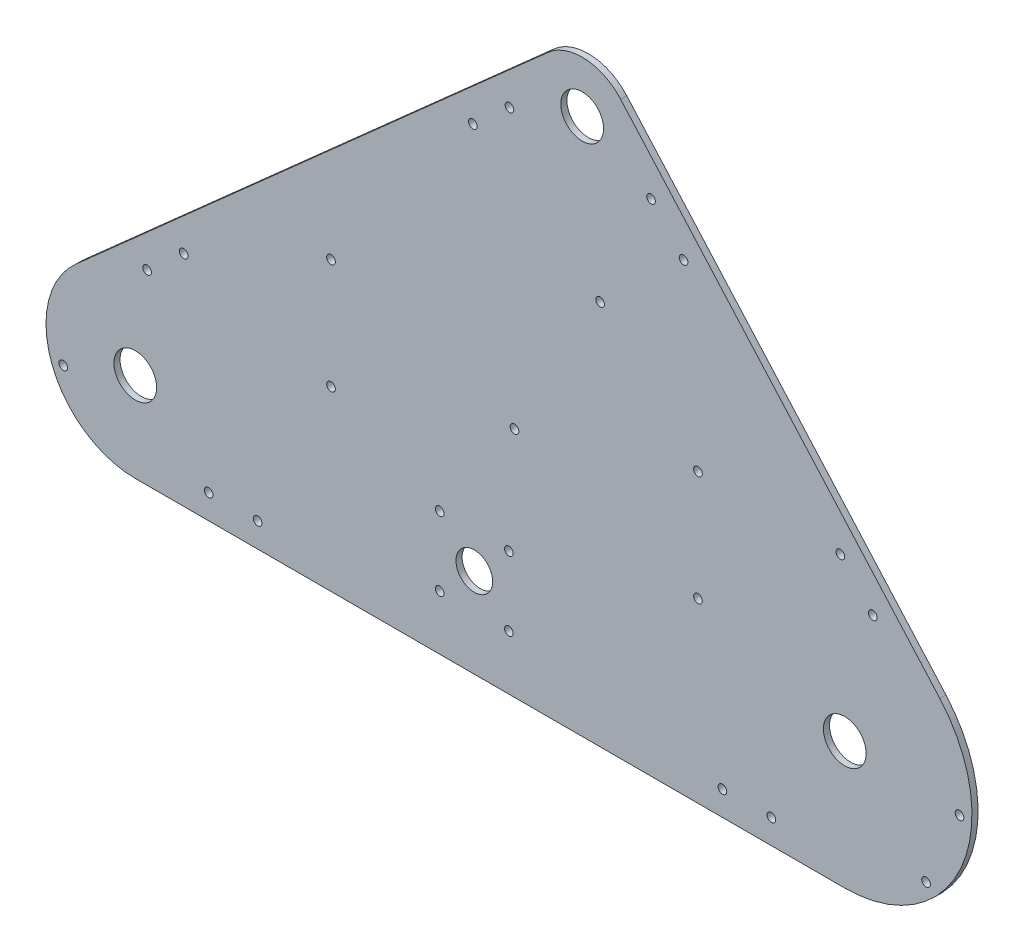
SolidWorks part; units mm, degrees
ref_plane "Front Plane" through (0, 0, 0) normal (0, 0, 1) x (1, 0, 0)
ref_plane "Top Plane" through (0, 0, 0) normal (0, 1, 0) x (1, 0, 0)
ref_plane "Right Plane" through (0, 0, 0) normal (1, 0, 0) x (0, 0, -1)
sketch "Sketch1" plane through (0, 0, 0) normal (0, 0, 1) x (1, 0, 0)
  line L4 (-188.2646, 81.0118) -> (56.8098, 298.7045)
  line L5 (-157.48, 0) -> (210.82, 0)
  line L9 (94.461, 296.4767) -> (260.194, 109.8976)
  line L10 (-157.48, 46.355) -> (18.5166, 46.355) construction
  line L11 (15.767, 41.5925) -> (21.2662, 41.5925) construction
  line L12 (21.2662, 41.5925) -> (24.0159, 46.355) construction
  line L13 (24.0159, 46.355) -> (21.2662, 51.1175) construction
  line L14 (21.2662, 51.1175) -> (15.767, 51.1175) construction
  line L15 (15.767, 51.1175) -> (13.0173, 46.355) construction
  line L16 (13.0173, 46.355) -> (15.767, 41.5925) construction
  line L19 (0.5561, 64.3155) -> (36.4771, 64.3155) construction
  line L20 (0.5561, 64.3155) -> (0.5561, 28.3945) construction
  line L21 (0.5561, 28.3945) -> (36.4771, 28.3945) construction
  line L22 (36.4771, 64.3155) -> (36.4771, 28.3945) construction
  line L23 (0.5561, 64.3155) -> (36.4771, 28.3945) construction
  line L24 (0.5561, 28.3945) -> (36.4771, 64.3155) construction
  arc A3 (-188.2646, 81.0118) -> (-157.48, 0) centre (-157.48, 46.355) ccw
  arc A4 (210.82, 0) -> (260.194, 109.8976) centre (210.82, 66.04) ccw
  arc A5 (94.461, 296.4767) -> (56.8098, 298.7045) centre (74.5215, 278.765) ccw
  circle A7 centre (-157.48, 46.355) radius 11.0998
  circle A8 centre (74.5215, 278.765) radius 11.0998
  circle A9 centre (210.82, 66.04) radius 11.0998
  circle A10 centre (18.5166, 46.355) radius 4.7625 construction
  circle A11 centre (18.5166, 46.355) radius 9.525
  point P0 (32.5752, -12.4288)
  point P2 (0, 0)
  point P29 (103.7153, 222.8013)
  point P51 (0, 0)
  point P53 (69.8235, 270.9052)
  point P54 (0, 0)
  point P55 (0, 0)
  dimension "D3" = 19.685
  dimension "D4" = 90
  dimension "D5" = 232.41
  dimension "D2" = 368.3
  dimension "D6" = 92.71
  dimension "D7" = 53.34
  dimension "D8" = 132.08
  dimension "D10" = 22.1996
  dimension "D11" = 9.525
  dimension "D14" = 50.8
  dimension "D12" = 19.05
  dimension "D13" = 175.9966
extrude "Boss-Extrude1" add sketch "Sketch1" along normal blind 3.175
hole_wizard "#8 Clearance Hole1" positions "Sketch4" profile "Sketch5" hole size "#8" standard "ANSI Inch"
sketch "Sketch4" plane through (0, 0, 3.175) normal (0, 0, 1) x (1, 0, 0)
  point P0 (36.4771, 64.3155)
  point P3 (36.4771, 28.3945)
  point P6 (0.5561, 28.3945)
  point P9 (0.5561, 64.3155)
sketch "Sketch5" plane through (36.4771, 64.3155, 3.175) normal (1, 0, 0) x (0, -1, 0)
  line L0 (0, 0) -> (0, 14.0507)
  line L1 (0, 14.0507) -> (2.2479, 12.7)
  line L2 (2.2479, 12.7) -> (2.2479, 0)
  line L5 (2.2479, 0) -> (0, 0)
  line L10 (0, 14.0507) -> (-2.2479, 12.7) construction
  line L11 (0, -6.35) -> (0, 107.95) construction
  dimension "Hole Dia." = 4.4958
  dimension "Hole Depth" = 12.7
  dimension "Drill Angle" = 118
sketch "Sketch6" plane through (0, 0, 3.175) normal (0, 0, 1) x (1, 0, 0)
  line L0 (56.8098, 298.7045) -> (-188.2646, 81.0118) construction
  line L1 (-157.48, 0) -> (210.82, 0) construction
  line L2 (260.194, 109.8976) -> (94.461, 296.4767) construction
  line L3 (-157.48, 46.355) -> (-188.2646, 81.0118) construction
  line L4 (-157.48, 46.355) -> (-157.48, 0) construction
  line L5 (210.82, 66.04) -> (210.82, 0) construction
  line L6 (210.82, 66.04) -> (260.194, 109.8976) construction
  line L7 (74.5215, 278.765) -> (56.8098, 298.7045) construction
  line L8 (94.461, 296.4767) -> (260.194, 109.8976) construction
  line L10 (74.5215, 278.765) -> (94.461, 296.4767) construction
  line L11 (39.37, 283.2132) -> (39.37, 0) construction
  line L12 (-188.2646, 81.0118) -> (56.8098, 298.7045) construction
  line L13 (-157.48, 0) -> (210.82, 0) construction
  line L14 (210.82, 66.04) -> (276.7447, 62.1393) construction
  line L15 (134.62, 92.075) -> (-55.88, 92.075) construction
  line L16 (134.62, 92.075) -> (134.62, 149.225) construction
  line L17 (134.62, 149.225) -> (-55.88, 149.225) construction
  line L18 (-55.88, 92.075) -> (-55.88, 149.225) construction
  line L19 (134.62, 92.075) -> (-55.88, 149.225) construction
  line L20 (134.62, 149.225) -> (-55.88, 92.075) construction
  line L21 (210.82, 66.04) -> (257.5173, 19.3427) construction
  line L22 (-157.48, 46.355) -> (-200.8119, 29.8888) construction
  arc A0 (210.82, 0) -> (260.194, 109.8976) centre (210.82, 66.04) ccw construction
  arc A1 (-188.2646, 81.0118) -> (-157.48, 0) centre (-157.48, 46.355) ccw construction
  point P0 (-119.38, 12.7)
  point P1 (-93.98, 12.7)
  point P2 (147.32, 12.7)
  point P3 (172.72, 12.7)
  point P4 (-151.3455, 96.8192)
  point P5 (-132.3555, 113.6875)
  point P6 (17.7689, 247.0388)
  point P7 (36.7589, 263.9071)
  point P8 (110.2685, 259.5575)
  point P9 (127.1368, 240.5675)
  point P12 (208.5283, 148.9385)
  point P13 (225.3966, 129.9484)
  point P44 (39.37, 120.65)
  point P50 (83.82, 200.025)
  point P60 (-194.876, 32.1444)
  point P61 (270.3947, 62.515)
  point P62 (253.0272, 23.8328)
  dimension "D28" = 6.35
  dimension "D1" = 12.7
  dimension "D2" = 12.7
  dimension "D3" = 12.7
  dimension "D4" = 12.7
  dimension "D5" = 12.7
  dimension "D6" = 25.4
  dimension "D7" = 38.1
  dimension "D8" = 38.1
  dimension "D9" = 25.4
  dimension "D10" = 25.4
  dimension "D11" = 12.7
  dimension "D12" = 12.7
  dimension "D13" = 25.4
  dimension "D14" = 38.1
  dimension "D15" = 12.7
  dimension "D16" = 12.7
  dimension "D17" = 38.1
  dimension "D18" = 25.4
  dimension "D19" = 25.4
  dimension "D20" = 38.1
  dimension "D21" = 38.1
  dimension "D22" = 196.85
  dimension "D23" = 57.15
  dimension "D24" = 190.5
  dimension "D25" = 120.65
  dimension "D26" = 45
  dimension "D27" = 45
  dimension "D29" = 6.35
  dimension "D30" = 6.35
  dimension "D31" = 50.8
  dimension "D32" = 50.8
hole_wizard "#8 Clearance Hole2" positions "Sketch7" profile "Sketch8" hole size "#8" standard "ANSI Inch" end condition through all
sketch "Sketch7" plane through (0, 0, 3.175) normal (0, 0, 1) x (1, 0, 0)
  point P0 (17.7689, 247.0388)
  point P3 (36.7589, 263.9071)
  point P6 (110.2685, 259.5575)
  point P9 (127.1368, 240.5675)
  point P12 (208.5283, 148.9385)
  point P15 (225.3966, 129.9484)
  point P18 (270.3947, 62.515)
  point P21 (253.0272, 23.8328)
  point P24 (172.72, 12.7)
  point P27 (147.32, 12.7)
  point P30 (-93.98, 12.7)
  point P33 (-119.38, 12.7)
  point P36 (-194.876, 32.1444)
  point P39 (-151.3455, 96.8192)
  point P42 (-132.3555, 113.6875)
  point P45 (-55.88, 149.225)
  point P48 (-55.88, 92.075)
  point P51 (134.62, 92.075)
  point P54 (134.62, 149.225)
  point P57 (83.82, 200.025)
  point P61 (39.37, 120.65)
sketch "Sketch8" plane through (17.7689, 247.0388, 3.175) normal (1, 0, 0) x (0, -1, 0)
  line L0 (0, 0) -> (0, 3.175)
  line L1 (0, 3.175) -> (2.2479, 3.175)
  line L2 (2.2479, 3.175) -> (2.2479, 0)
  line L5 (2.2479, 0) -> (0, 0)
  line L11 (0, -6.35) -> (0, 107.95) construction
  dimension "Thru Hole Dia." = 4.4958
  dimension "Thru Hole Depth" = 3.175
